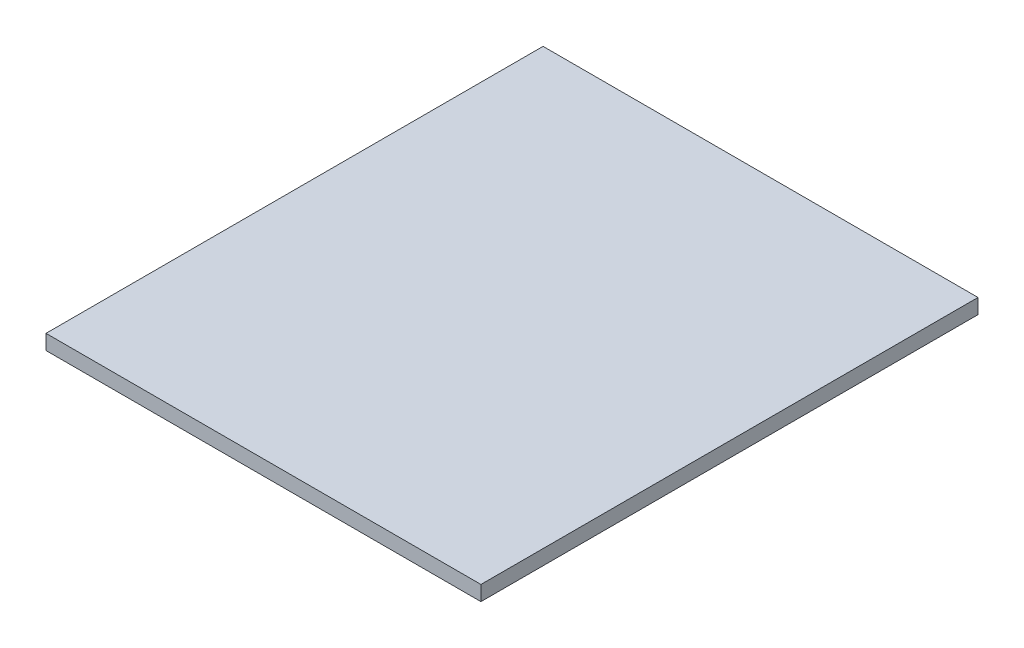
SolidWorks part; units mm, degrees
material "Резина"
ref_plane "Спереди" through (0, 0, 0) normal (0, 0, 1) x (1, 0, 0)
ref_plane "Сверху" through (0, 0, 0) normal (0, 1, 0) x (1, 0, 0)
ref_plane "Справа" through (0, 0, 0) normal (1, 0, 0) x (0, 0, -1)
sketch "Эскиз1" plane through (0, 0, 0) normal (0, 1, 0) x (1, 0, 0)
  line L1 (-61.2412, 49.6837) -> (638.7588, 49.6837)
  line L2 (-61.2412, 49.6837) -> (-61.2412, -750.3163)
  line L3 (-61.2412, -750.3163) -> (638.7588, -750.3163)
  line L4 (638.7588, 49.6837) -> (638.7588, -750.3163)
  dimension "D1" = 700
  dimension "D2" = 800
extrude "Бобышка-Вытянуть1" add sketch "Эскиз1" along normal blind 24
